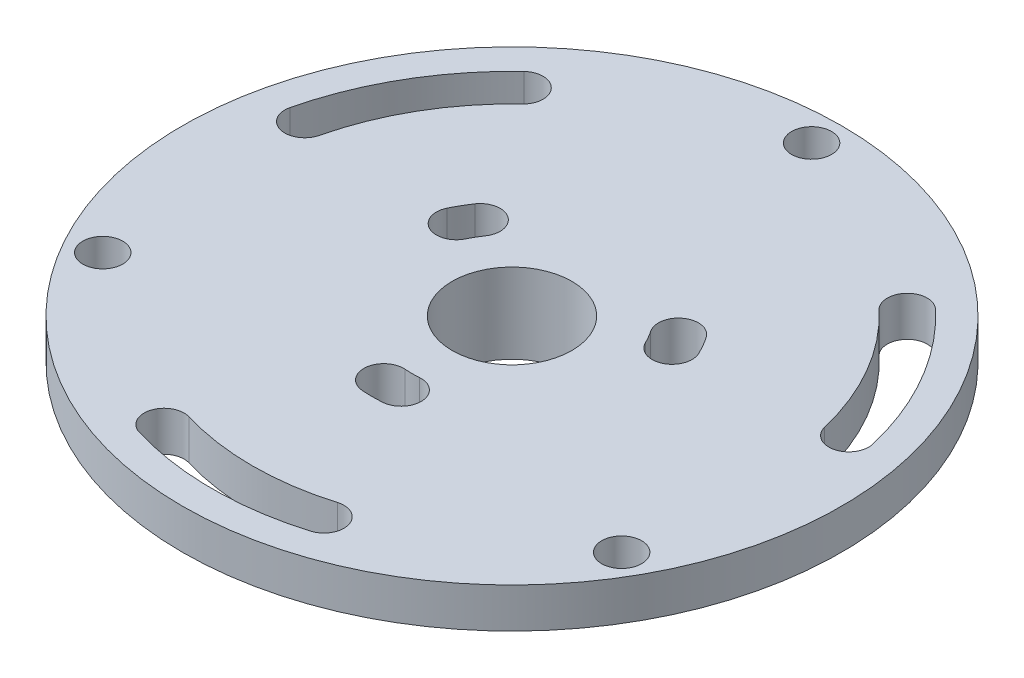
SolidWorks part; units mm, degrees
ref_plane "前视基准面" through (0, 0, 0) normal (0, 0, 1) x (1, 0, 0)
ref_plane "上视基准面" through (0, 0, 0) normal (0, 1, 0) x (1, 0, 0)
ref_plane "右视基准面" through (0, 0, 0) normal (1, 0, 0) x (0, 0, -1)
sketch "草图1" plane through (0, 0, 0) normal (0, 1, 0) x (1, 0, 0)
  line L0 (0, 0) -> (0, 30) construction
  circle A0 centre (0, 0) radius 16.5
  circle A1 centre (0, 15) radius 1
  circle A2 centre (0, 0) radius 3
  circle A3 centre (12.9904, -7.5) radius 1
  circle A4 centre (-12.9904, -7.5) radius 1
  point P14 (0, 0)
  dimension "D2" = 33
  dimension "D3" = 2
  dimension "D4" = 6
  dimension "D5" = 3
  dimension "D1" = 15
extrude "凸台-拉伸1" add sketch "草图1" along normal blind 2
sketch "草图2" plane through (0, 0, 0) normal (0, -1, 0) x (1, 0, 0)
  circle A0 centre (0, 0) radius 4
  circle A1 centre (0, 0) radius 3
  dimension "D1" = 8
extrude "凸台-拉伸2" add sketch "草图2" along normal blind 2
sketch "草图3" plane through (0, 2, 0) normal (0, 1, 0) x (1, 0, 0)
  line L0 (0, 0) -> (26.0417, 15.0352) construction
  line L1 (0, 0) -> (27.3738, 0) construction
  arc A0 (9.6187, 10.1725) -> (13.619, 3.2438) centre (0, 0) cw construction
  arc A1 (14.5918, 3.4755) -> (10.3058, 10.8991) centre (0, 0) ccw
  arc A2 (12.6462, 3.0121) -> (8.9317, 9.4459) centre (0, 0) ccw
  arc A3 (12.6462, 3.0121) -> (14.5918, 3.4755) centre (13.619, 3.2438) ccw
  arc A4 (10.3058, 10.8991) -> (8.9317, 9.4459) centre (9.6187, 10.1725) ccw
  arc A5 (4.9652, 3.3686) -> (5.3998, 2.6157) centre (0, 0) cw construction
  arc A6 (6.2998, 3.0516) -> (5.7927, 3.93) centre (0, 0) ccw
  arc A7 (4.4999, 2.1797) -> (4.1376, 2.8071) centre (0, 0) ccw
  arc A8 (4.4999, 2.1797) -> (6.2998, 3.0516) centre (5.3998, 2.6157) ccw
  arc A9 (5.7927, 3.93) -> (4.1376, 2.8071) centre (4.9652, 3.3686) ccw
  arc A11 (4.0003, -13.4163) -> (-4.0003, -13.4163) centre (0, 0) cw construction
  arc A12 (-4.286, -14.3746) -> (4.286, -14.3746) centre (0, 0) ccw
  arc A13 (-3.7146, -12.458) -> (3.7146, -12.458) centre (0, 0) ccw
  arc A14 (-3.7146, -12.458) -> (-4.286, -14.3746) centre (-4.0003, -13.4163) ccw
  arc A15 (4.286, -14.3746) -> (3.7146, -12.458) centre (4.0003, -13.4163) ccw
  arc A16 (0.4347, -5.9842) -> (-0.4347, -5.9842) centre (0, 0) cw construction
  arc A17 (-0.5071, -6.9816) -> (0.5071, -6.9816) centre (0, 0) ccw
  arc A18 (-0.3622, -4.9869) -> (0.3622, -4.9869) centre (0, 0) ccw
  arc A19 (-0.3622, -4.9869) -> (-0.5071, -6.9816) centre (-0.4347, -5.9842) ccw
  arc A20 (0.5071, -6.9816) -> (0.3622, -4.9869) centre (0.4347, -5.9842) ccw
  arc A21 (-13.619, 3.2438) -> (-9.6187, 10.1725) centre (0, 0) cw construction
  arc A22 (-10.3058, 10.8991) -> (-14.5918, 3.4755) centre (0, 0) ccw
  arc A23 (-8.9317, 9.4459) -> (-12.6462, 3.0121) centre (0, 0) ccw
  arc A24 (-8.9317, 9.4459) -> (-10.3058, 10.8991) centre (-9.6187, 10.1725) ccw
  arc A25 (-14.5918, 3.4755) -> (-12.6462, 3.0121) centre (-13.619, 3.2438) ccw
  arc A26 (-5.3998, 2.6157) -> (-4.9652, 3.3686) centre (0, 0) cw construction
  arc A27 (-5.7927, 3.93) -> (-6.2998, 3.0516) centre (0, 0) ccw
  arc A28 (-4.1376, 2.8071) -> (-4.4999, 2.1797) centre (0, 0) ccw
  arc A29 (-4.1376, 2.8071) -> (-5.7927, 3.93) centre (-4.9652, 3.3686) ccw
  arc A30 (-6.2998, 3.0516) -> (-4.4999, 2.1797) centre (-5.3998, 2.6157) ccw
  point P4 (12.1244, 7)
  point P9 (5.1962, 3)
  point P27 (0, -14)
  point P32 (0, -6)
  point P41 (-12.1244, 7)
  point P46 (-5.1962, 3)
  point P53 (0, 0)
  dimension "D3" = 1
  dimension "D4" = 14
  dimension "D5" = 1
  dimension "D1" = 30
  dimension "D2" = 6
  dimension "D6" = 3
extrude "切除-拉伸1" cut sketch "草图3" against normal blind 2
